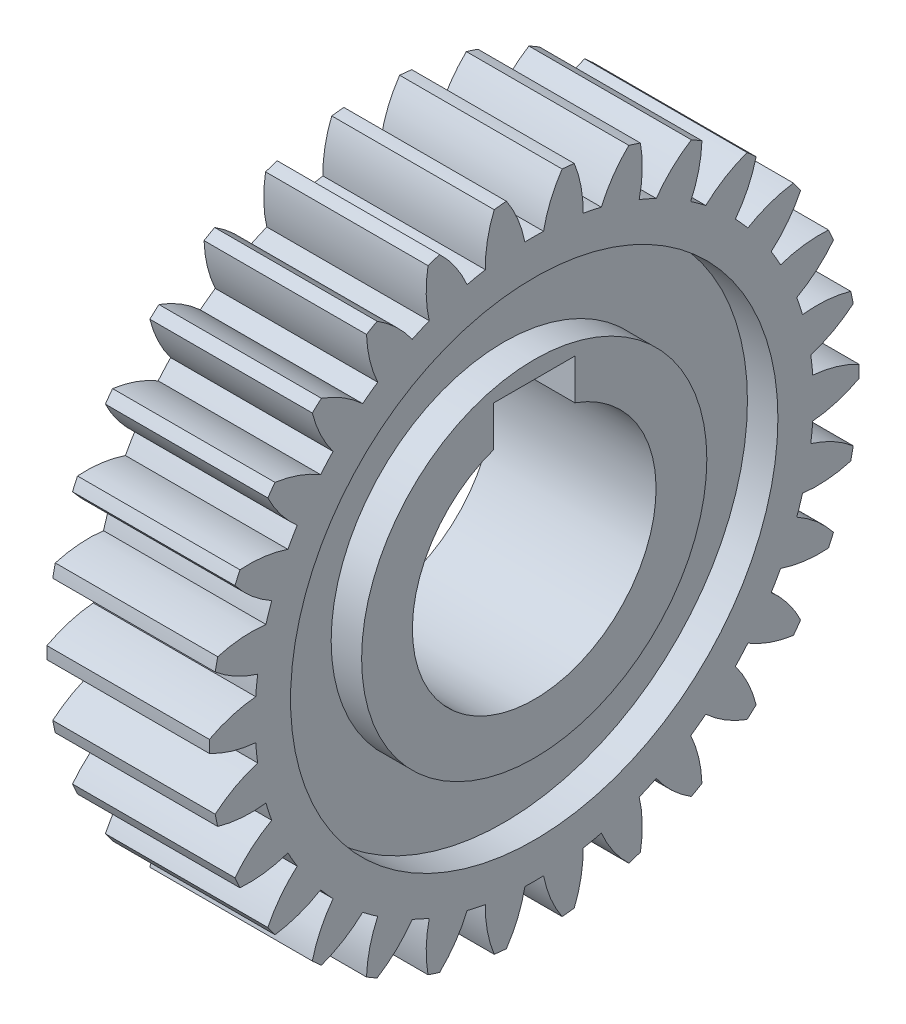
SolidWorks part; units mm, degrees
ref_plane "Plane1" through (0, 0, 0) normal (0, 0, 1) x (1, 0, 0)
ref_plane "Plane2" through (0, 0, 0) normal (0, 1, 0) x (1, 0, 0)
ref_plane "Plane3" through (0, 0, 0) normal (1, 0, 0) x (0, 0, -1)
sketch "HoldingSke" plane through (0, 0, 0) normal (0, 1, 0) x (1, 0, 0)
  line L0 (0, 0) -> (0.433, -0.25)
  line L1 (-15, 0) -> (100, 0) construction
  line L2 (0, 0) -> (-2.1039, 2.3779)
  line L3 (0, 0) -> (-11.863, 4.5341)
  line L4 (0, 0) -> (7.479, 4.318)
  line L5 (0, 0) -> (-46.8476, -17.4728)
  line L6 (0, 0) -> (-0.829, -0.5593)
  line L7 (-2.1039, 2.3779) -> (8.6586, 51.2059)
  line L8 (-76.2, 54.61) -> (-75.9, 54.61)
  line L9 (-71.009, 38.7566) -> (-53.1078, 45.2721)
  line L10 (-76.2, 71.12) -> (104.1128, 71.12)
  line L11 (0, 0) -> (-1, 0)
  line L12 (-76.2, 101.6) -> (-76.133, 101.6)
  line L13 (24.9733, 27.94) -> (52.9518, 28.4284)
  line L14 (24.9733, 27.94) -> (24.9743, 27.94)
  line L15 (24.9733, 27.94) -> (100.4006, 29.5858)
  line L16 (-63.627, -2) -> (-12.827, -2)
  circle A0 centre (0, 0) radius 1
  circle A1 centre (0, 0) radius 27.499
  circle A2 centre (0, 0) radius 37.5
  circle A3 centre (0, 0) radius 1
  dimension "MHD" = 54.998
  dimension "Hub_dia" = 75
  dimension "Bore" = 2
  dimension "MBD" = 2
  dimension "Num_teeth" = 30
  dimension "Pitch" = 0.5
  dimension "Overall_len" = 50
  dimension "Show_teeth" = 30
  dimension "Thickness" = 1
  dimension "OAL" = 50.0001
  dimension "T_dim" = 0.3
  dimension "Ap" = 20
  dimension "H" = 19.05
  dimension "Pitch_radius" = 180.3128
  dimension "Width" = 1
  dimension "Backlash" = 0.067
  dimension "Addendum_fac" = 1
  dimension "Dedendum_fac" = 1.25
  dimension "Clearance_fac" = 0.25
  dimension "Dedendum_add" = 0.001
  dimension "Module" = 2
sketch "BasProSke" plane through (0, 0, 0) normal (0, 1, 0) x (1, 0, 0)
  line L0 (-10, 0) -> (60, 0) construction
  line L1 (0, 0) -> (0, 32)
  line L2 (0, 0) -> (16, 0)
  line L3 (16, 0) -> (16, 32)
  line L4 (16, 32) -> (0, 32)
  point P3 (0, 0)
  point P5 (0, 0)
  dimension "Thickness" = 16
  dimension "Diameter" = 64
revolve "Base-Revolve" add sketch "BasProSke" angle 360 about L0
sketch "TooCutSke" plane through (0, 0, 0) normal (1, 0, 0) x (0, 0, -1)
  line L1 (0, 0) -> (0, 107) construction
  line L2 (0, 0) -> (-1.6873, 29.9525) construction
  line L3 (0, 0) -> (-6.2643, 59.6013) construction
  line L4 (-1.6873, 29.9525) -> (-3.1322, 29.8007) construction
  arc A0 (0.9186, 27.4837) -> (-0.9186, 27.4837) centre (0, 0) ccw
  arc A1 (2.7618, 31.9061) -> (-2.7618, 31.9061) centre (0, 0) ccw
  circle A2 centre (0, 0) radius 30 construction
  circle A3 centre (0, 0) radius 28.1908 construction
  arc A4 (-0.9186, 27.4837) -> (-2.7618, 31.9061) centre (-12.6936, 25.1712) ccw
  arc A5 (2.7618, 31.9061) -> (0.9186, 27.4837) centre (12.6936, 25.1712) ccw
  dimension "Root_dia" = 54.998
  dimension "Overcut_dia" = 64.0508
  dimension "Pitch_dia" = 60
  dimension "Base_dia" = 56.3816
  dimension "Flank_rad" = 12
  dimension "Half_ang" = 6
  dimension "Half_CT" = 1.4528
extrude "ToothCut" cut sketch "TooCutSke" along normal through all
fillet "Breaks" [suppressed] radius 0.04
fillet "RootFillets" [suppressed] radius 0.501
pattern_circular "TeethCuts" count 30 every 12 about axis through (-10, 0, 0) along (1, 0, 0) of "ToothCut", "RootFillets", "Breaks"
sketch "HubNeaOneSke" plane through (0, 0, 0) normal (-1, 0, 0) x (0, 0, 1)
  circle A0 centre (0, 0) radius 27.499
  dimension "Diameter" = 54.998
extrude "HubNearOne" [suppressed] add sketch "HubNeaOneSke" along normal blind 34.0001
sketch "HubNeaBotSke" plane through (0, 0, 0) normal (-1, 0, 0) x (0, 0, 1)
  circle A0 centre (0, 0) radius 27.499
  dimension "Diameter" = 54.998
extrude "HubNearBoth" [suppressed] add sketch "HubNeaBotSke" along normal blind 17
ref_plane "FarPln" through (16, 0, 0) normal (1, 0, 0) x (0, 0, -1)
sketch "HubFarSke" plane through (16, 0, 0) normal (1, 0, 0) x (0, 0, -1)
  circle A0 centre (0, 0) radius 27.499
  dimension "Diameter" = 54.998
extrude "HubFar" [suppressed] add sketch "HubFarSke" along normal blind 17
sketch "BorSke" plane through (0, 0, 0) normal (1, 0, 0) x (0, 0, -1)
  circle A0 centre (0, 0) radius 12
  dimension "Diameter" = 24
extrude "Bore" cut sketch "BorSke" along normal mid plane 100.0001
sketch "KeySke" plane through (0, 0, 0) normal (1, 0, 0) x (0, 0, -1)
  line L0 (-0.4, 0) -> (-0.4, 1.3)
  line L1 (-0.4, 1.3) -> (0.4, 1.3)
  line L2 (0.4, 1.3) -> (0.4, 0)
  line L3 (0, 0) -> (0, 34) construction
  line L4 (-0.4, 0) -> (0.4, 0)
  dimension "Offset" = 1.3
  dimension "Width" = 0.8
extrude "Keyway" [suppressed] cut sketch "KeySke" along normal mid plane 100.0001
pattern_circular "Keyway2" [suppressed] count 2 every 90 about axis through (-10, 0, 0) along (1, 0, 0)
sketch "Schizzo3" plane through (16, 0, 0) normal (1, 0, 0) x (0, 0, -1)
  circle A0 centre (0, 0) radius 17
  circle A1 centre (0, 0) radius 24
  dimension "D1" = 34
  dimension "D2" = 48
extrude "Taglio-Estrusione2" cut sketch "Schizzo3" against normal blind 3
ref_plane "Piano1" through (8, 0, 0) normal (-1, 0, 0) x (0, 0, 1)
mirror "Specchia1" about plane through (8, 0, 0) normal (-1, 0, 0) of "Taglio-Estrusione2"
sketch "Schizzo4" plane through (0, 0, 0) normal (-1, 0, 0) x (0, 0, 1)
  line L1 (-4, 15.3) -> (4, 15.3)
  line L2 (-4, 15.3) -> (-4, 11.3137)
  line L4 (4, 15.3) -> (4, 11.3137)
  circle A0 centre (0, 0) radius 12 construction
  arc A1 (4, 11.3137) -> (-4, 11.3137) centre (0, 0) ccw
  point P2 (0, 0)
  point P4 (0, 0)
  point P8 (0, 0)
  point P11 (0, 0)
  point P12 (0, 0)
  dimension "D1" = 15.3
  dimension "D2" = 8
  dimension "D3" = 3.9863
extrude "Taglio-Estrusione3" cut sketch "Schizzo4" against normal through all
equation "' \"Module@HoldingSke\" = 6.35"
equation "' \"Num_teeth@HoldingSke\" = 12"
equation "' \"Ap@HoldingSke\" =  20"
equation "' \"Ap@HoldingSke\" = 20"
equation "' \"Width@HoldingSke\" = 0.5 * 25.4"
equation "' \"Hub_dia@HoldingSke\"= 1 * 25.4"
equation "' \"Hub_dia@HoldingSke\" = 1 * 25.4"
equation "' \"Overall_len@HoldingSke\" = 1.0 * 25.4"
equation "' \"Bore@HoldingSke\" = 0.75 * 25.4"
equation "' \"T_dim@HoldingSke\" = 0.1 * 25.4"
equation "' \"Width@KeySke\" = 0.25 * 25.4"
equation "' \"Show_teeth@HoldingSke\" = 13"
equation "' \"Backlash@HoldingSke\" = 0.009 * 25.4"
equation "' \"Addendum_fac@HoldingSke\" = 1.0"
equation "' \"Dedendum_fac@HoldingSke\" = 1.25"
equation "' \"Dedendum_add@HoldingSke\" = 0.00005 * 25.4"
equation "' \"Clearance_fac@HoldingSke\" = 0.25"
equation "\"Pitch@HoldingSke\" = 1 / \"Module@HoldingSke\""
equation "\"Overcut_dia@TooCutSke\" = (\"Num_teeth@HoldingSke\" + 2 * \"Addendum_fac@HoldingSke\") / \"Pitch@HoldingSke\" + 0.002 * 25.4"
equation "\"Pitch_dia@TooCutSke\" = \"Num_teeth@HoldingSke\" / \"Pitch@HoldingSke\""
equation "\"Base_dia@TooCutSke\" = \"Num_teeth@HoldingSke\" / \"Pitch@HoldingSke\" * cos((\"Ap@HoldingSke\"  * 3.14159265 / 180))"
equation "\"Root_dia@TooCutSke\" = (\"Num_teeth@HoldingSke\" + 2) / \"Pitch@HoldingSke\" - 2 * (\"Addendum_fac@HoldingSke\" + \"Dedendum_fac@HoldingSke\") / \"Pitch@HoldingSke\" - \"Dedendum_add@HoldingSke\" * 2"
equation "\"Half_ang@TooCutSke\" = 180 / \"Num_teeth@HoldingSke\""
equation "\"Half_CT@TooCutSke\" = \"Num_teeth@HoldingSke\" / \"Pitch@HoldingSke\" * sin((3.14159265 / 2 / \"Num_teeth@HoldingSke\")) / 2 - 7 * \"Backlash@HoldingSke\" / 4"
equation "\"Flank_rad@TooCutSke\" = \"Num_teeth@HoldingSke\" / \"Pitch@HoldingSke\" / 5"
equation "\"Radius@RootFillets\" = \"Clearance_fac@HoldingSke\" / \"Pitch@HoldingSke\" + \"Dedendum_add@HoldingSke\""
equation "\"Break_rad@Breaks\" = 0.02 / \"Pitch@HoldingSke\""
equation "\"Thickness@HoldingSke\" = \"Width@HoldingSke\""
equation "\"OAL@HoldingSke\" = \"Thickness@HoldingSke\""
equation "\"MHD@HoldingSke\" = (\"Num_teeth@HoldingSke\" + 2) / \"Pitch@HoldingSke\" - 2 * (\"Addendum_fac@HoldingSke\" + \"Dedendum_fac@HoldingSke\")  / \"Pitch@HoldingSke\" - \"Dedendum_add@HoldingSke\" * 2"
equation "\"MBD@HoldingSke\" = (\"Num_teeth@HoldingSke\" + 2) / \"Pitch@HoldingSke\" - 2 * (\"Addendum_fac@HoldingSke\" + \"Dedendum_fac@HoldingSke\")  / \"Pitch@HoldingSke\" - \"Dedendum_add@HoldingSke\" * 2 - 0.002 * 25.4"
equation "\"MHD@HoldingSke\" = ((sgn( \"MHD@HoldingSke\" - \"Hub_dia@HoldingSke\" )-1)*( \"MHD@HoldingSke\" - \"Hub_dia@HoldingSke\" ))/-2+ \"Hub_dia@HoldingSke\""
equation "\"MBD@HoldingSke\" = ((sgn( \"MBD@HoldingSke\" - \"Bore@HoldingSke\" )-1)*( \"MBD@HoldingSke\" - \"Bore@HoldingSke\" ))/-2+ \"Bore@HoldingSke\""
equation "\"OAL@HoldingSke\" = ((sgn( \"OAL@HoldingSke\" - \"Overall_len@HoldingSke\" )+1)*( \"OAL@HoldingSke\" - \"Overall_len@HoldingSke\" ))/2 + \"Overall_len@HoldingSke\" + 0.000002 * 25.4"
equation "\"Num_teeth@TeethCuts\" = int( \"Show_teeth@HoldingSke\" ) + 1"
equation "\"Num_teeth@TeethCuts\" = ((sgn( \"Num_teeth@TeethCuts\" - \"Num_teeth@HoldingSke\" )-1)*( \"Num_teeth@TeethCuts\" - \"Num_teeth@HoldingSke\" ))/-2+ \"Num_teeth@HoldingSke\""
equation "\"Num_teeth@TeethCuts\" = ((sgn( \"Num_teeth@TeethCuts\" - 2.0)+1)*( \"Num_teeth@TeethCuts\" - 2.0))/2 +2.0"
equation "\"Angle@TeethCuts\" = 360.0 / \"Num_teeth@HoldingSke\""
equation "\"Diameter@BasProSke\" = (\"Num_teeth@HoldingSke\" + 2 * \"Addendum_fac@HoldingSke\") / \"Pitch@HoldingSke\""
equation "' \"Fillet_rad@BasProSke\" =  \"Thickness@HoldingSke\" * 0.05"
equation "' \"Fillet_rad@BasProSke\" = \"Thickness@HoldingSke\" * 0.05"
equation "\"MHD@HoldingSke\" = ((sgn( \"MHD@HoldingSke\" - \"Root_dia@TooCutSke\" )-1)*( \"MHD@HoldingSke\" - \"Root_dia@TooCutSke\" ))/-2+ \"Root_dia@TooCutSke\""
equation "\"Diameter@HubNeaOneSke\" = \"MHD@HoldingSke\""
equation "\"Length@HubNearOne\" = \"OAL@HoldingSke\" - \"Thickness@BasProSke\""
equation "\"Diameter@HubNeaBotSke\" = \"MHD@HoldingSke\""
equation "\"Length@HubNearBoth\" = ( \"OAL@HoldingSke\" - \"Thickness@BasProSke\" ) / 2.0"
equation "\"Thickness@FarPln\" = \"Thickness@BasProSke\""
equation "\"Diameter@HubFarSke\" = \"MHD@HoldingSke\""
equation "\"Length@HubFar\" = ( \"OAL@HoldingSke\" - \"Thickness@BasProSke\" ) / 2.0"
equation "\"D1@Bore\" = \"OAL@HoldingSke\" * 2.0"
equation "\"D1@Keyway\" = \"OAL@HoldingSke\" * 2.0"
equation "\"Offset@KeySke\" = \"T_dim@HoldingSke\" + \"MBD@HoldingSke\" / 2.0"
